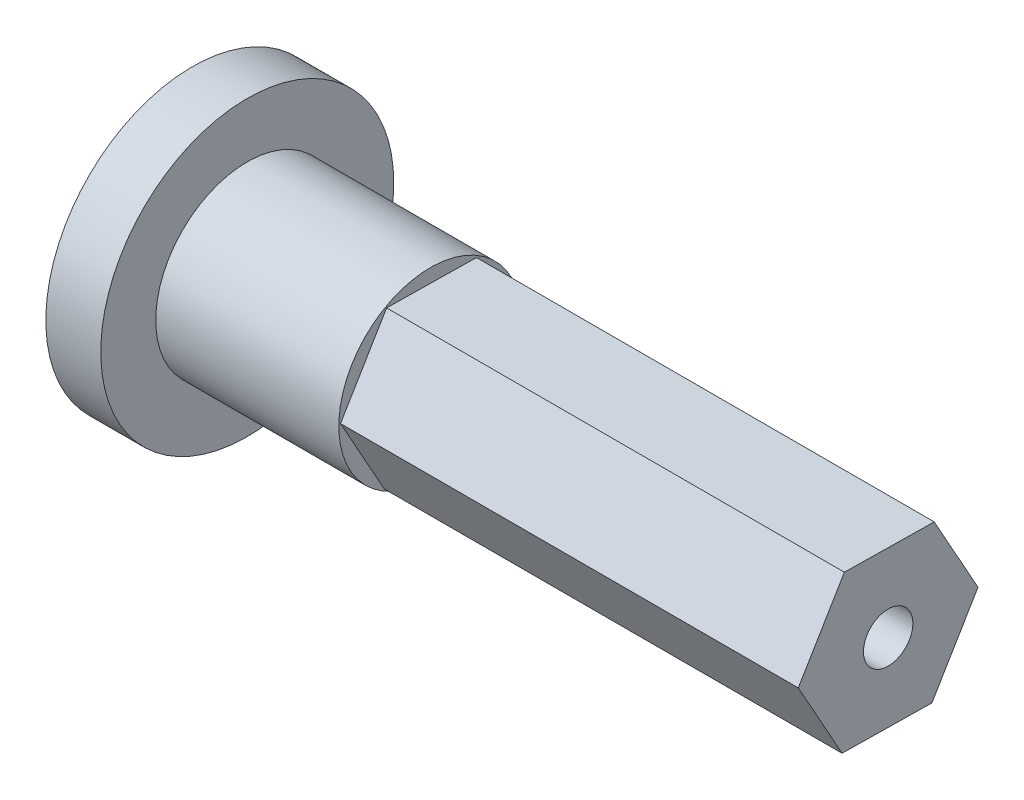
SolidWorks part; units mm, degrees
ref_plane "Front Plane" through (0, 0, 0) normal (0, 0, 1) x (1, 0, 0)
ref_plane "Top Plane" through (0, 0, 0) normal (0, 1, 0) x (1, 0, 0)
ref_plane "Right Plane" through (0, 0, 0) normal (1, 0, 0) x (0, 0, -1)
sketch "Sketch2" plane through (0, 0, 0) normal (1, 0, 0) x (0, 0, -1)
  circle A0 centre (0, 0) radius 8
  dimension "D1" = 16
extrude "Boss-Extrude1" add sketch "Sketch2" along normal blind 3
sketch "Sketch3" plane through (3, 0, 0) normal (1, 0, 0) x (0, 0, -1)
  circle A0 centre (0, 0) radius 5
  dimension "D1" = 10
extrude "Boss-Extrude2" add sketch "Sketch3" along normal blind 10
sketch "Sketch5" plane through (0, 0, 0) normal (-1, 0, 0) x (0, 0, 1)
  line L6 (0, -2.3094) -> (2, -1.1547)
  line L11 (2, -1.1547) -> (2, 1.1547)
  line L12 (2, 1.1547) -> (0, 2.3094)
  line L13 (0, 2.3094) -> (-2, 1.1547)
  line L14 (-2, 1.1547) -> (-2, -1.1547)
  line L15 (-2, -1.1547) -> (0, -2.3094)
  circle A0 centre (0, 0) radius 2 construction
  dimension "D1" = 4
sketch "Sketch6" plane through (13, 0, 0) normal (1, 0, 0) x (0, 0, -1)
  line L1 (2.39, -4.2862) -> (4.9069, -0.0733)
  line L2 (4.9069, -0.0733) -> (2.5169, 4.2129)
  line L3 (2.5169, 4.2129) -> (-2.39, 4.2862)
  line L4 (-2.39, 4.2862) -> (-4.9069, 0.0733)
  line L5 (-4.9069, 0.0733) -> (-2.5169, -4.2129)
  line L6 (-2.5169, -4.2129) -> (2.39, -4.2862)
  circle A0 centre (0, 0) radius 4.25 construction
  dimension "D1" = 8.5
extrude "Boss-Extrude3" add sketch "Sketch6" along normal blind 25
sketch "Sketch8" plane through (38, 0, 0) normal (1, 0, 0) x (0, 0, -1)
  circle A0 centre (0, 0) radius 1.35
  dimension "D1" = 2.7
extrude "Cut-Extrude3" cut sketch "Sketch8" against normal blind 10
extrude "Cut-Extrude5" cut sketch "Sketch5" against normal blind 23.5
